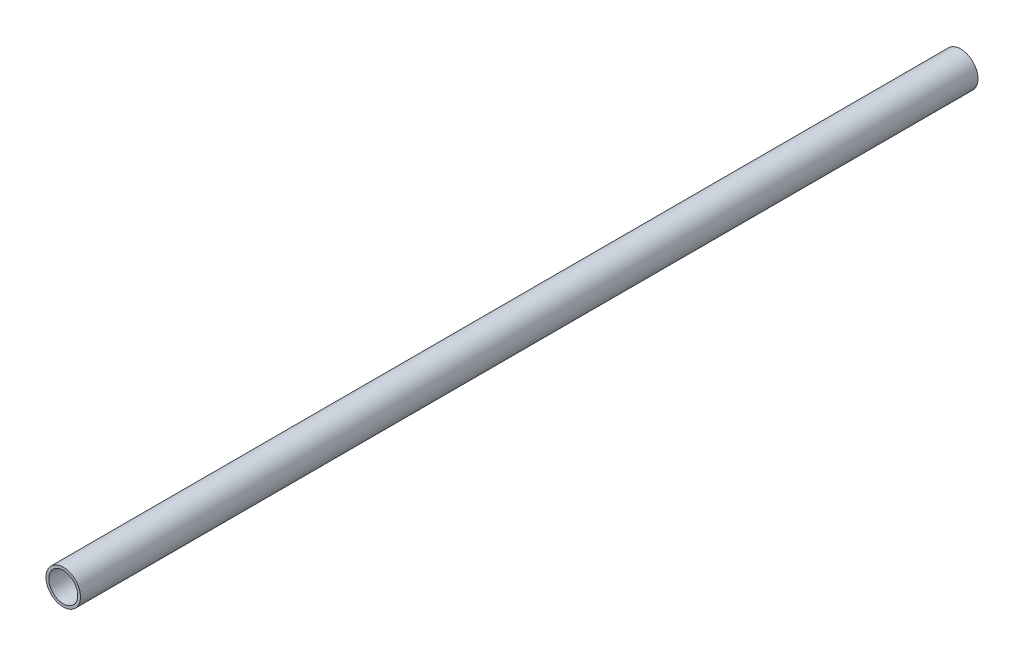
SolidWorks part; units mm, degrees
ref_plane "Alzado" through (0, 0, 0) normal (0, 0, 1) x (1, 0, 0)
ref_plane "Planta" through (0, 0, 0) normal (0, 1, 0) x (1, 0, 0)
ref_plane "Vista lateral" through (0, 0, 0) normal (1, 0, 0) x (0, 0, -1)
sketch "Croquis1" plane through (0, 0, 0) normal (0, 0, 1) x (1, 0, 0)
  circle A0 centre (0, 0) radius 12.5
  circle A1 centre (0, 0) radius 10.5
  dimension "D1" = 25
  dimension "D2" = 2
extrude "Saliente-Extruir1" add sketch "Croquis1" along normal blind 650
